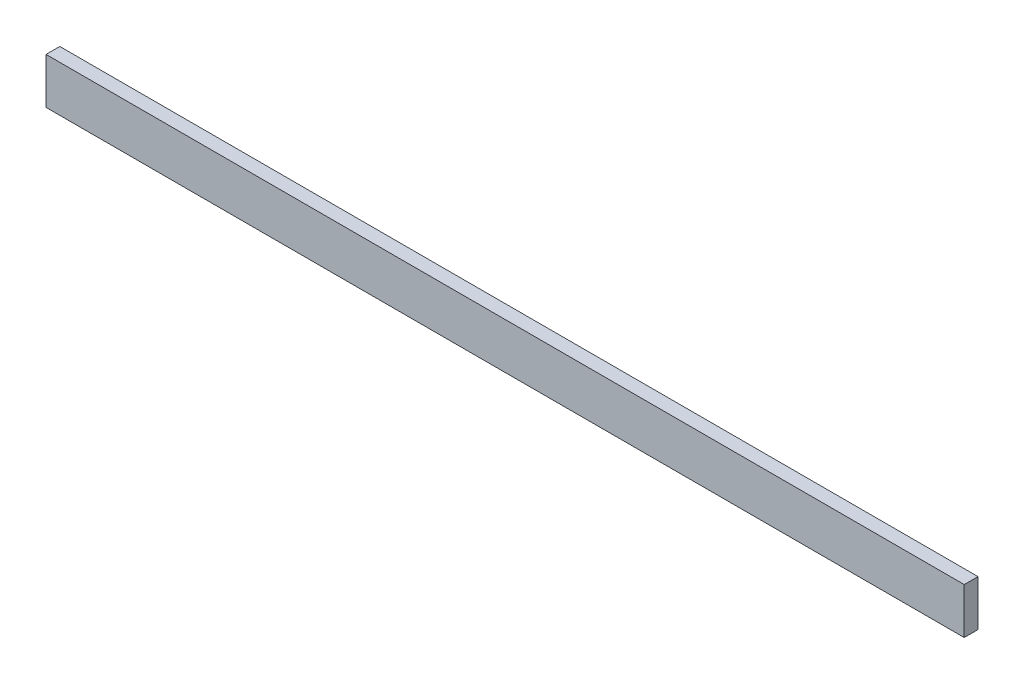
SolidWorks part; units mm, degrees
material "Plywood"
ref_plane "Plan de face" through (0, 0, 0) normal (0, 0, 1) x (1, 0, 0)
ref_plane "Plan de dessus" through (0, 0, 0) normal (0, 1, 0) x (1, 0, 0)
ref_plane "Plan de droite" through (0, 0, 0) normal (1, 0, 0) x (0, 0, -1)
sketch "Esquisse1" plane through (0, 0, 0) normal (0, 0, 1) x (1, 0, 0)
  line L1 (0, 0) -> (200, 0)
  line L2 (0, 0) -> (0, 10)
  line L3 (0, 10) -> (200, 10)
  line L4 (200, 0) -> (200, 10)
  dimension "D1" = 10
  dimension "D2" = 200
extrude "Boss.-Extru.1" add sketch "Esquisse1" along normal blind 3
